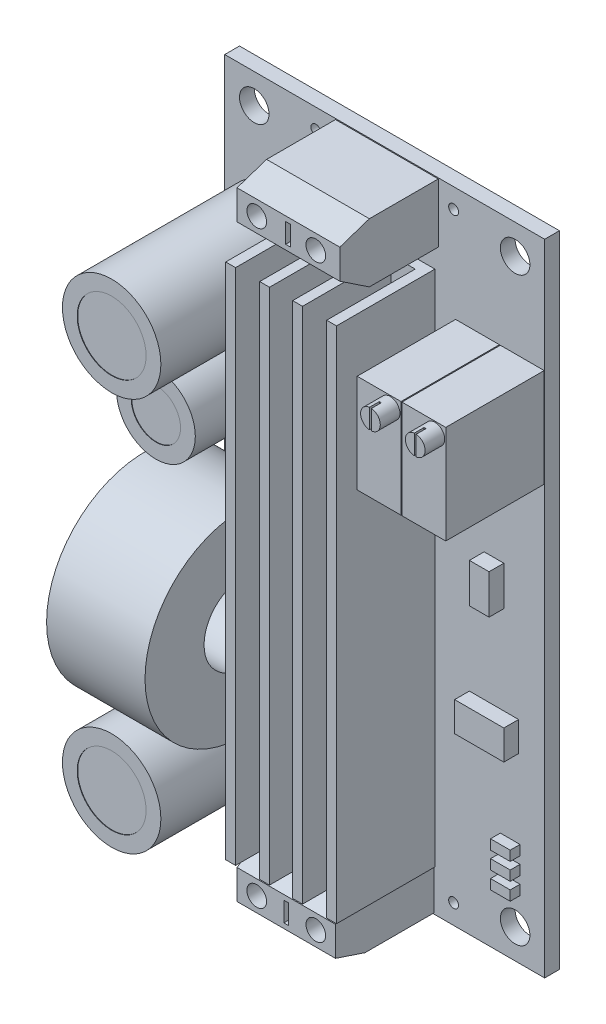
SolidWorks part; units mm, degrees
ref_plane "Front" through (0, 0, 0) normal (0, 0, 1) x (1, 0, 0)
ref_plane "Top" through (0, 0, 0) normal (0, 1, 0) x (1, 0, 0)
ref_plane "Right" through (0, 0, 0) normal (1, 0, 0) x (0, 0, -1)
sketch "草图1" plane through (0, 0, 0) normal (0, 0, 1) x (1, 0, 0)
  line L1 (0, 0) -> (32.5, 0)
  line L2 (0, 0) -> (0, 65)
  line L3 (0, 65) -> (32.5, 65)
  line L4 (32.5, 0) -> (32.5, 65)
  circle A0 centre (3, 62) radius 1.5
  circle A1 centre (29.5, 3) radius 1.5
  circle A2 centre (3, 3) radius 1.5
  circle A3 centre (29.5, 62) radius 1.5
  dimension "D3" = 3
  dimension "D4" = 3
  dimension "D5" = 3
  dimension "D6" = 3
  dimension "D1" = 65
  dimension "D2" = 32.5
extrude "凸台-拉伸1" add sketch "草图1" along normal blind 1.5
sketch "草图2" plane through (0, 0, 1.5) normal (0, 0, 1) x (1, 0, 0)
  line L0 (0, 0) -> (32.5, 0) construction
  line L1 (11.25, 0.1) -> (21.25, 0.1)
  line L2 (11.25, 0.1) -> (11.25, 6.1)
  line L3 (11.25, 6.1) -> (21.25, 6.1)
  line L4 (21.25, 0.1) -> (21.25, 6.1)
  line L5 (32.5, 65) -> (0, 65) construction
  line L6 (11.25, 58.9) -> (21.6913, 58.9)
  line L7 (11.25, 58.9) -> (11.25, 64.9)
  line L8 (11.25, 64.9) -> (21.6913, 64.9)
  line L9 (21.6913, 58.9) -> (21.6913, 64.9)
  point P6 (16.25, 0.1)
  point P7 (16.25, 0)
  dimension "D1" = 10
  dimension "D2" = 6
  dimension "D3" = 0.1
  dimension "D4" = 0
  dimension "D5" = 6
  dimension "D6" = 0.1
extrude "凸台-拉伸2" add sketch "草图2" along normal blind 10
sketch "草图3" plane through (21.25, 0, 0) normal (1, 0, 0) x (0, 0, -1)
  line L0 (-11.5, 0.1) -> (-11.5, 1.1)
  line L1 (-11.5, 0.1) -> (-11.5, 6.1) construction
  line L2 (-11.5, 1.1) -> (-8.5, 0.1)
  line L3 (-11.5, 0.1) -> (-1.5, 0.1) construction
  line L4 (-8.5, 0.1) -> (-11.2108, 0.1)
  line L5 (-11.2108, 0.1) -> (-11.5, 0.1)
  line L6 (-11.5, 4.1) -> (-11.5, 6.1)
  line L7 (-11.5, 6.1) -> (-8.5, 6.1)
  line L8 (-11.5, 6.1) -> (-1.5, 6.1) construction
  line L9 (-8.5, 6.1) -> (-11.5, 4.1)
  dimension "D1" = 1
  dimension "D2" = 3
  dimension "D3" = 2
extrude "切除-拉伸1" cut sketch "草图3" against normal through all
sketch "草图4" plane through (21.6913, 0, 0) normal (1, 0, 0) x (0, 0, -1)
  line L0 (-11.5, 58.9) -> (-11.5, 60.9)
  line L1 (-11.5, 58.9) -> (-11.5, 64.9) construction
  line L2 (-11.5, 60.9) -> (-8.5, 58.9)
  line L3 (-11.5, 58.9) -> (-1.5, 58.9) construction
  line L4 (-8.5, 58.9) -> (-11.5, 58.9)
  line L5 (-11.5, 63.9) -> (-11.5, 64.9)
  line L6 (-11.5, 64.9) -> (-8.5, 64.9)
  line L7 (-11.5, 64.9) -> (-1.5, 64.9) construction
  line L8 (-8.5, 64.9) -> (-11.5, 63.9)
  dimension "D1" = 2
  dimension "D2" = 3
  dimension "D3" = 1
  dimension "D4" = 3
extrude "切除-拉伸2" cut sketch "草图4" against normal through all
sketch "草图5" plane through (0, 0, 1.5) normal (0, 0, 1) x (1, 0, 0)
  line L1 (23.4526, 43.4215) -> (27.9026, 43.4215)
  line L2 (23.4526, 43.4215) -> (23.4526, 53.4215)
  line L3 (23.4526, 53.4215) -> (27.9026, 53.4215)
  line L4 (27.9026, 43.4215) -> (27.9026, 53.4215)
  line L5 (28.0026, 43.4215) -> (32.4526, 43.4215)
  line L6 (28.0026, 43.4215) -> (28.0026, 53.4215)
  line L7 (28.0026, 53.4215) -> (32.4526, 53.4215)
  line L8 (32.4526, 43.4215) -> (32.4526, 53.4215)
  dimension "D1" = 10
  dimension "D2" = 4.45
  dimension "D3" = 4.45
  dimension "D4" = 0.1
extrude "凸台-拉伸3" add sketch "草图5" along normal blind 10
sketch "草图6" plane through (0, 0, 11.5) normal (0, 0, 1) x (1, 0, 0)
  line L0 (27.9026, 53.4215) -> (23.4526, 53.4215) construction
  line L1 (27.9026, 43.4215) -> (27.9026, 53.4215) construction
  line L2 (32.4526, 43.4215) -> (32.4526, 53.4215) construction
  circle A0 centre (26.8026, 52.3215) radius 1
  circle A1 centre (31.3526, 52.3215) radius 1
  dimension "D1" = 2
  dimension "D2" = 1.1
  dimension "D3" = 1.1
  dimension "D4" = 1.1
extrude "凸台-拉伸4" add sketch "草图6" along normal blind 2
sketch "草图7" plane through (0, 0, 13.5) normal (0, 0, 1) x (1, 0, 0)
  line L1 (26.7026, 51.0672) -> (26.9026, 51.0672)
  line L2 (26.7026, 51.0672) -> (26.7026, 53.6349)
  line L3 (26.7026, 53.6349) -> (26.9026, 53.6349)
  line L4 (26.9026, 51.0672) -> (26.9026, 53.6349)
  line L5 (31.2526, 50.9395) -> (31.4526, 50.9395)
  line L6 (31.2526, 50.9395) -> (31.2526, 53.8393)
  line L7 (31.2526, 53.8393) -> (31.4526, 53.8393)
  line L8 (31.4526, 50.9395) -> (31.4526, 53.8393)
  circle A0 centre (26.8026, 52.3215) radius 1 construction
  circle A1 centre (31.3526, 52.3215) radius 1 construction
  dimension "D1" = 0.1
  dimension "D2" = 0.1
  dimension "D3" = 0.1
  dimension "D4" = 0.1
extrude "切除-拉伸3" cut sketch "草图7" against normal blind 1
sketch "草图8" plane through (0, 0, 1.5) normal (0, 0, 1) x (1, 0, 0)
  line L0 (0, 65) -> (0, 0) construction
  line L1 (0, 0) -> (32.5, 0) construction
  line L2 (32.5, 65) -> (0, 65) construction
  circle A0 centre (5.01, 11) radius 5
  circle A1 centre (5.01, 51) radius 5
  dimension "D1" = 5.01
  dimension "D2" = 11
  dimension "D3" = 14
extrude "凸台-拉伸5" add sketch "草图8" along normal blind 16.5
sketch "草图9" plane through (0, 0, 1.5) normal (0, 0, 1) x (1, 0, 0)
  circle A0 centre (5.01, 41.9) radius 4
  circle A1 centre (5.01, 51) radius 5 construction
  dimension "D1" = 9.1
extrude "凸台-拉伸6" add sketch "草图9" along normal blind 12
ref_plane "基准面1" through (2, 0, 0) normal (-1, 0, 0) x (0, 0, 1)
sketch "草图10" plane through (2, 0, 0) normal (-1, 0, 0) x (0, 0, 1)
  line L0 (1.5, 65) -> (1.5, 0) construction
  line L1 (8.5, 0.1) -> (1.5, 0.1) construction
  circle A0 centre (11.6, 26.1) radius 10
  circle A1 centre (11.6, 26.1) radius 4
  dimension "D1" = 10.1
  dimension "D2" = 26
extrude "凸台-拉伸7" add sketch "草图10" against normal blind 10 separate body
sketch "草图11" plane through (0, 0, 1.5) normal (0, 0, 1) x (1, 0, 0)
  line L0 (0, 0) -> (32.5, 0) construction
  line L1 (21.25, 1.1) -> (21.25, 4.1) construction
  line L2 (32.5, 65) -> (0, 65) construction
  line L3 (11.25, 64.9) -> (11.25, 58.9) construction
  circle A0 centre (23.25, 2) radius 0.5
  circle A1 centre (9.25, 63) radius 0.5
  circle A2 centre (23.25, 63) radius 0.5
  circle A3 centre (9.25, 2) radius 0.5
  dimension "D1" = 2
  dimension "D2" = 2
  dimension "D3" = 2
  dimension "D4" = 2
extrude "切除-拉伸4" cut sketch "草图11" against normal through all
ref_plane "基准面2" through (0, 0, 3.5) normal (0, 0, 1) x (1, 0, 0)
sketch "草图14" plane through (0, 0, 3.5) normal (0, 0, 1) x (1, 0, 0)
  line L0 (11.25, 6.1) -> (21.25, 6.1) construction
  line L1 (23.3526, 6.2) -> (12.1, 6.2)
  line L2 (23.3526, 6.2) -> (23.3526, 58.8)
  line L3 (23.3526, 58.8) -> (12.1, 58.8)
  line L4 (12.1, 6.2) -> (12.1, 58.8)
  line L5 (11.25, 58.9) -> (21.6913, 58.9) construction
  line L6 (12, 16.1) -> (12, 36.1) construction
  line L7 (23.4526, 53.4215) -> (23.4526, 43.4215) construction
  dimension "D1" = 0.1
  dimension "D2" = 0.1
  dimension "D3" = 0.1
  dimension "D4" = 0.1
extrude "凸台-拉伸8" add sketch "草图14" along normal blind 1 separate body
sketch "草图15" plane through (0, 0, 4.5) normal (0, 0, 1) x (1, 0, 0)
  line L0 (23.3526, 58.8) -> (12.1, 58.8) construction
  line L1 (23.3526, 6.2) -> (22.3526, 6.2)
  line L2 (23.3526, 6.2) -> (23.3526, 58.8)
  line L3 (23.3526, 58.8) -> (22.3526, 58.8)
  line L4 (22.3526, 6.2) -> (22.3526, 58.8)
  line L5 (12.1, 6.2) -> (23.3526, 6.2) construction
  line L6 (12.1, 58.8) -> (13.1, 58.8)
  line L7 (12.1, 58.8) -> (12.1, 6.2)
  line L8 (12.1, 6.2) -> (13.1, 6.2)
  line L9 (13.1, 58.8) -> (13.1, 6.2)
  line L11 (19.9026, 6.2) -> (18.9026, 6.2)
  line L12 (19.9026, 6.2) -> (19.9026, 58.8)
  line L13 (19.9026, 58.8) -> (18.9026, 58.8)
  line L14 (18.9026, 6.2) -> (18.9026, 58.8)
  line L15 (16.55, 6.2) -> (15.55, 6.2)
  line L16 (16.55, 6.2) -> (16.55, 58.8)
  line L17 (16.55, 58.8) -> (15.55, 58.8)
  line L18 (15.55, 6.2) -> (15.55, 58.8)
  dimension "D1" = 1
  dimension "D2" = 1
  dimension "D3" = 1
  dimension "D4" = 1
  dimension "D5" = 2.45
  dimension "D6" = 2.45
extrude "凸台-拉伸9" add sketch "草图15" along normal blind 9
sketch "草图16" plane through (0, 0, 1.5) normal (0, 0, 1) x (1, 0, 0)
  line L0 (23.3526, 6.2) -> (23.3526, 58.8) construction
  line L1 (29.8526, 18.4215) -> (24.8526, 18.4215)
  line L2 (29.8526, 18.4215) -> (29.8526, 21.4215)
  line L3 (29.8526, 21.4215) -> (24.8526, 21.4215)
  line L4 (24.8526, 18.4215) -> (24.8526, 21.4215)
  line L5 (28.3526, 30.4215) -> (26.3526, 30.4215)
  line L6 (28.3526, 30.4215) -> (28.3526, 34.4215)
  line L7 (28.3526, 34.4215) -> (26.3526, 34.4215)
  line L8 (26.3526, 30.4215) -> (26.3526, 34.4215)
  line L9 (23.4526, 43.4215) -> (27.9026, 43.4215) construction
  dimension "D1" = 5
  dimension "D2" = 3
  dimension "D3" = 4
  dimension "D4" = 2
  dimension "D5" = 3
  dimension "D6" = 1.5
  dimension "D7" = 9
  dimension "D8" = 9
extrude "凸台-拉伸10" add sketch "草图16" along normal blind 1.5
sketch "草图17" plane through (0, 0, 1.5) normal (0, 0, 1) x (1, 0, 0)
  line L0 (32.5, 0) -> (32.5, 65) construction
  line L1 (30, 6) -> (28, 6)
  line L2 (30, 6) -> (30, 7)
  line L3 (30, 7) -> (28, 7)
  line L4 (28, 6) -> (28, 7)
  line L6 (30, 7.75) -> (28, 7.75)
  line L7 (30, 7.75) -> (30, 8.75)
  line L8 (30, 8.75) -> (28, 8.75)
  line L9 (28, 7.75) -> (28, 8.75)
  line L10 (30, 9.5) -> (28, 9.5)
  line L11 (30, 9.5) -> (30, 10.5)
  line L12 (30, 10.5) -> (28, 10.5)
  line L13 (28, 9.5) -> (28, 10.5)
  circle A0 centre (29.5, 3) radius 1.5 construction
  dimension "D1" = 2
  dimension "D2" = 1
  dimension "D3" = 2.5
  dimension "D4" = 3
  dimension "D5" = 1
  dimension "D6" = 1
  dimension "D7" = 0.75
  dimension "D8" = 0.75
extrude "凸台-拉伸11" add sketch "草图17" along normal blind 1
sketch "草图18" plane through (0, 0, 18) normal (0, 0, 1) x (1, 0, 0)
  circle A0 centre (5.01, 11) radius 3.5
  circle A1 centre (5.01, 51) radius 3.5
extrude "切除-拉伸5" cut sketch "草图18" against normal blind 0.05
sketch "草图19" plane through (0, 0, 13.5) normal (0, 0, 1) x (1, 0, 0)
  circle A0 centre (5.01, 41.9) radius 2.5
extrude "切除-拉伸6" cut sketch "草图19" against normal blind 0.05
sketch "草图20" plane through (0, 0, 11.5) normal (0, 0, 1) x (1, 0, 0)
  line L0 (11.25, 1.1) -> (21.25, 1.1) construction
  line L1 (21.25, 0.1) -> (21.25, 6.1) construction
  line L2 (11.25, 4.1) -> (11.25, 1.1) construction
  line L3 (21.25, 4.1) -> (11.25, 4.1) construction
  line L4 (16.5, 1.6) -> (16, 1.6)
  line L5 (16.5, 1.6) -> (16.5, 3.6)
  line L6 (16.5, 3.6) -> (16, 3.6)
  line L7 (16, 1.6) -> (16, 3.6)
  line L8 (11.25, 60.9) -> (21.6913, 60.9) construction
  line L9 (16.6913, 61.4) -> (16.1913, 61.4)
  line L10 (16.6913, 61.4) -> (16.6913, 63.4)
  line L11 (16.6913, 63.4) -> (16.1913, 63.4)
  line L12 (16.1913, 61.4) -> (16.1913, 63.4)
  line L13 (21.6913, 60.9) -> (21.6913, 63.9) construction
  circle A0 centre (19.25, 2.6) radius 1
  circle A1 centre (13.25, 2.6) radius 1
  circle A2 centre (19.25, 62.4) radius 1
  circle A3 centre (13.25, 62.4) radius 1
  point P14 (16.25, 1.6)
  point P15 (16.25, 3.6)
  point P18 (16.25, 4.1)
  dimension "D1" = 1.5
  dimension "D2" = 2
  dimension "D3" = 2
  dimension "D8" = 0.5
  dimension "D4" = 0.5
  dimension "D5" = 2
  dimension "D6" = 0.5
  dimension "D7" = 0
  dimension "D9" = 2
  dimension "D10" = 0.5
  dimension "D11" = 5
extrude "切除-拉伸7" cut sketch "草图20" against normal blind 2
equation "\".1、\"=0.551994"
